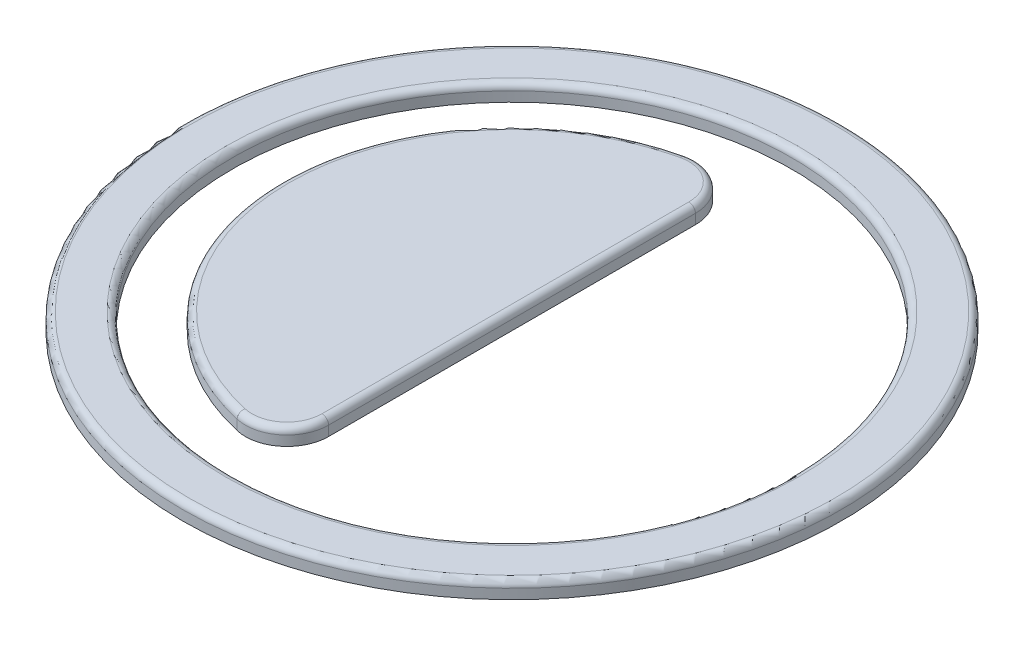
SolidWorks part; units mm, degrees
ref_plane "Front Plane" through (0, 0, 0) normal (0, 0, 1) x (1, 0, 0)
ref_plane "Top Plane" through (0, 0, 0) normal (0, 1, 0) x (1, 0, 0)
ref_plane "Right Plane" through (0, 0, 0) normal (1, 0, 0) x (0, 0, -1)
sketch "Эскиз1" plane through (0, 0, 0) normal (0, 1, 0) x (1, 0, 0)
  line L1 (0, 5.5656) -> (0, -5.5656)
  arc A0 (-1.542, 6.797) -> (0, 5.5656) centre (-1.2626, 5.5656) cw
  arc A1 (-1.542, -6.797) -> (-1.542, 6.797) centre (0, 0) cw
  arc A2 (0, -5.5656) -> (-1.542, -6.797) centre (-1.2626, -5.5656) cw
  circle A3 centre (0, 0) radius 8.4903
  circle A4 centre (0, 0) radius 10
  point P2 (0, 0)
  dimension "D1" = 20
  dimension "D2" = 1.2626
extrude "Бобышка-Вытянуть1" add sketch "Эскиз1" along normal blind 0.5 contours A2 L1 A0 A1 | A4 A3
fillet "Скругление1" radius 0.2 4 edges at (-0.4747, 0.5, -6.5523) (-6.9697, 0.5, 0) (-0.4747, 0.5, 6.5523) (0, 0.5, 0)
fillet "Скругление2" radius 0.2 1 edges at (0, 0.5, 8.4903)
fillet "Скругление3" radius 0.2 1 edges at (0, 0.5, 10)
